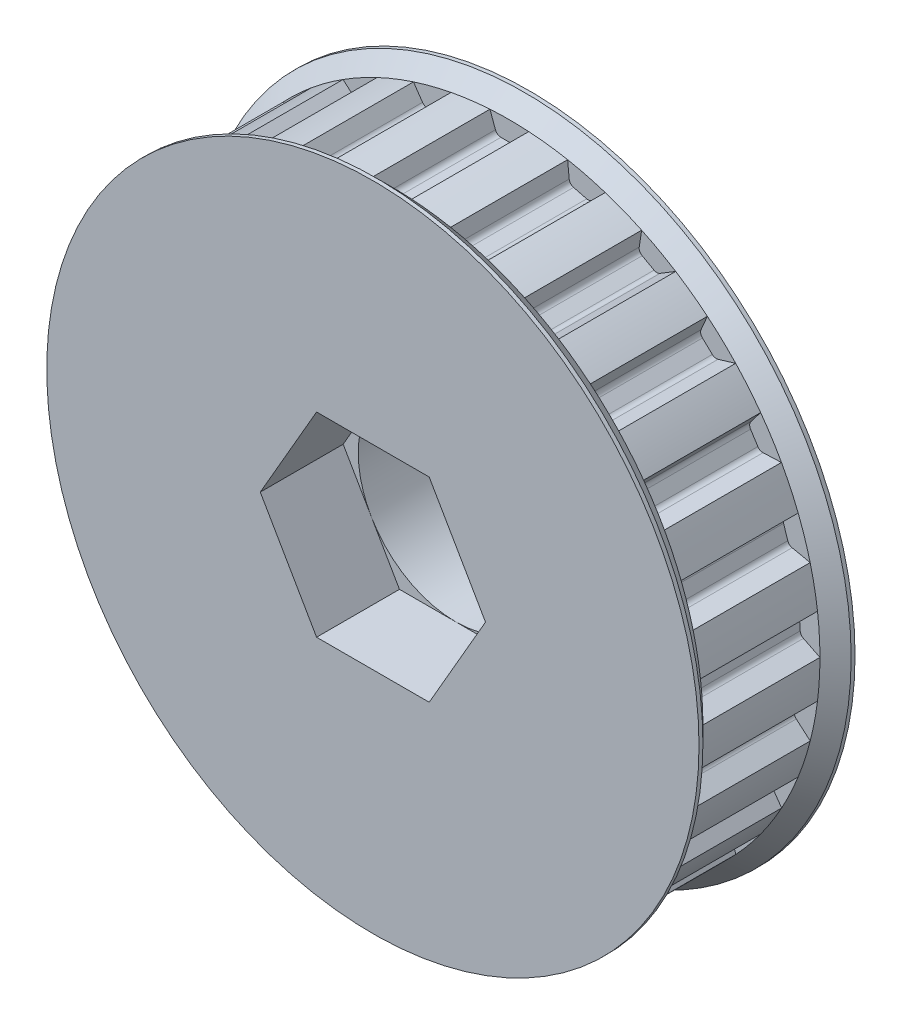
SolidWorks part; units mm, degrees
extrude "BasePulley" add sketch "Sketch1" against normal blind 7.62
sketch "Sketch1" plane through (0, 0, 0) normal (0, 0, 1) x (1, 0, 0)
  circle A0 centre (0, 0) radius 20.2184
  dimension "Outside_dia" = 40.4368
revolve "Flange" add sketch "Sketch2" angle 360 about L11
sketch "Sketch2" plane through (0, 0, 0) normal (1, 0, 0) x (0, 0, -1)
  line L0 (7.62, 20.2184) -> (8.636, 21.2344)
  line L1 (8.636, 21.2344) -> (8.89, 21.2344)
  line L2 (3.81, 0) -> (3.81, 66.675) construction
  line L4 (8.89, 21.2344) -> (8.89, 0)
  line L5 (0, 20.2184) -> (-1.016, 21.2344)
  line L6 (7.62, -20.2184) -> (7.62, 20.2184) construction
  line L7 (-1.016, 21.2344) -> (-1.27, 21.2344)
  line L9 (-1.27, 21.2344) -> (-1.27, 0)
  line L10 (7.62, 20.2184) -> (0, 20.2184)
  line L11 (0, 0) -> (38.2092, 0) construction
  line L12 (7.62, 0) -> (0, 0) construction
  line L13 (-1.27, 0) -> (8.89, 0)
  point P4 (11.1715, 20.1676)
  point P19 (-0.7366, 19.1516)
  point P20 (0, 0)
  dimension "D1" = 3.81
  dimension "D3" = 1.27
  dimension "D2" = 20.2184
  dimension "Flange_ht" = 1.016
  dimension "D4" = 45
ref_plane "Plane1" through (0, 0, 0) normal (0, 0, 1) x (1, 0, 0)
ref_plane "Plane2" through (0, 0, 0) normal (0, 1, 0) x (1, 0, 0)
ref_plane "Plane3" through (0, 0, 0) normal (1, 0, 0) x (0, 0, -1)
other "Configuration Table"
sketch "Clipboard" plane through (0, 0, 0) normal (0, 0, 1) x (1, 0, 0)
  line L0 (0, 0) -> (2.6416, 0)
  line L1 (0, 0) -> (34.8061, 15.4967)
  line L2 (0, 0) -> (34.8061, -15.4967)
ref_plane "Plane4" through (0, 0, -3.81) normal (0, 0, 1) x (1, 0, 0)
sketch "Sketch3" plane through (0, 0, -3.81) normal (0, 0, 1) x (1, 0, 0)
  line L0 (-1.2827, 20.2184) -> (-1.2827, 45.6184)
  line L1 (1.2827, 20.2184) -> (1.2827, 45.6184)
  line L2 (0, 0) -> (0, 20.2184) construction
  line L3 (-1.2827, 20.2184) -> (1.2827, 20.2184) construction
  line L4 (-0.5537, 18.9484) -> (0.3295, 18.9484)
  line L5 (1.2827, 20.2184) -> (0.6595, 19.1389)
  line L6 (-1.2827, 20.2184) -> (-0.9117, 19.1991)
  line L7 (1.2827, 45.6184) -> (-1.2827, 45.6184)
  arc A0 (0.3295, 18.9484) -> (0.6595, 19.1389) centre (0.3295, 19.3294) ccw
  arc A2 (-0.9117, 19.1991) -> (-0.5537, 18.9484) centre (-0.5537, 19.3294) ccw
  dimension "Grv_rad_bot" = 0.381
  dimension "Grv_ang" = 50
  dimension "D3" = 20
  dimension "Grv_width" = 2.5654
  dimension "D4" = 25.4
  dimension "D1" = 20.2184
  dimension "Grv_depth" = 1.27
extrude "Groove" cut sketch "Sketch3" against normal mid plane 7.62
pattern_circular "Grooves" count 25 over 360 about axis through (0, 0, 0) along (0, 0, 1) of "Groove"
sketch "Sketch4" plane through (0, 0, 0) normal (1, 0, 0) x (0, 0, -1)
  line L0 (0, 0) -> (47.6781, 0) construction
  line L1 (7.62, 0) -> (0, 0) construction
  line L2 (0, 0) -> (-30.48, 0)
  line L3 (-30.48, 0) -> (-30.48, 6.35)
  line L4 (-30.48, 6.35) -> (0, 6.35)
  line L5 (0, 6.35) -> (0, 0)
  line L6 (-30.48, -6.35) -> (0, -6.35) construction
revolve "BaseHub" [suppressed] add sketch "Sketch4" angle 360 about L0
sketch "BorSke" [suppressed] plane through (0, 0, 27.686) normal (0, 0, 1) x (1, 0, 0)
  circle A0 centre (0, 0) radius 1.1913
extrude "Bore" [suppressed] cut sketch "BorSke" against normal through all
sketch "KeySke" [suppressed] plane through (0, 0, 27.686) normal (0, 0, 1) x (1, 0, 0)
  line L0 (0.127, 1.4503) -> (0.127, 0)
  line L1 (0.127, 1.4503) -> (-0.127, 1.4503)
  line L2 (-0.127, 1.4503) -> (-0.127, 0)
  line L3 (-0.127, 0) -> (0.127, 0)
  line L4 (0, 31.75) -> (0, -3.175) construction
  dimension "Width" = 7.62
extrude "Keyway" [suppressed] cut sketch "KeySke" against normal through all
pattern_circular "Keyway2" [suppressed] count 2 every 90
sketch "Sketch5" plane through (0, 0, -8.89) normal (0, 0, -1) x (-1, 0, 0)
  circle A0 centre (0, 0) radius 6.35
  dimension "D1" = 12.7
extrude "Cut-Extrude1" cut sketch "Sketch5" against normal blind 4.7625
sketch "Sketch6" plane through (0, 0, -4.1275) normal (0, 0, -1) x (-1, 0, 0)
  line L1 (3.6662, 6.35) -> (-3.6662, 6.35)
  line L2 (-3.6662, 6.35) -> (-7.3323, 0)
  line L3 (-7.3323, 0) -> (-3.6662, -6.35)
  line L4 (-3.6662, -6.35) -> (3.6662, -6.35)
  line L5 (3.6662, -6.35) -> (7.3323, 0)
  line L6 (7.3323, 0) -> (3.6662, 6.35)
  circle A1 centre (0, 0) radius 6.35 construction
  dimension "D1" = 12.7
extrude "Cut-Extrude3" cut sketch "Sketch6" against normal through all
equation "\"D1@Plane4\" = \"Width@BasePulley\" / 2"
equation "\"D1@Groove\" = \"Width@BasePulley\""
equation "\"D1@Sketch3\" = \"Outside_dia@Sketch1\" / 2"
equation "\"D1@Sketch2\" = \"Width@BasePulley\" / 2"
equation "\"D2@Sketch2\" = \"Outside_dia@Sketch1\" / 2"
equation "\"Num_grvs@Clipboard\" = int( \"Num_grvs@Clipboard\" )"
equation "\"Show_grvs@Clipboard\" = int( \"Show_grvs@Clipboard\" )"
equation "\"Show_grvs@Clipboard\" = ((sgn( \"Show_grvs@Clipboard\" - \"Num_grvs@Clipboard\" )-1)*( \"Show_grvs@Clipboard\" - \"Num_grvs@Clipboard\" ))/-2+ \"Num_grvs@Clipboard\""
equation "\"Show_grvs@Clipboard\" = ((sgn( \"Show_grvs@Clipboard\" - 1.0)+1)*( \"Show_grvs@Clipboard\" - 1.0))/2 +1.0"
equation "\"Num_grvs@Grooves\"=25"
equation "\"Offset@KeySke\" = \"T_dim@Clipboard\" - \"Diameter@BorSke\" / 2.0"
equation "\"OAL@Clipboard\" = \"Overall_len@Clipboard\""
equation "\"Hub_depth@Sketch4\" = \"OAL@Clipboard\" - \"Width@BasePulley\""
